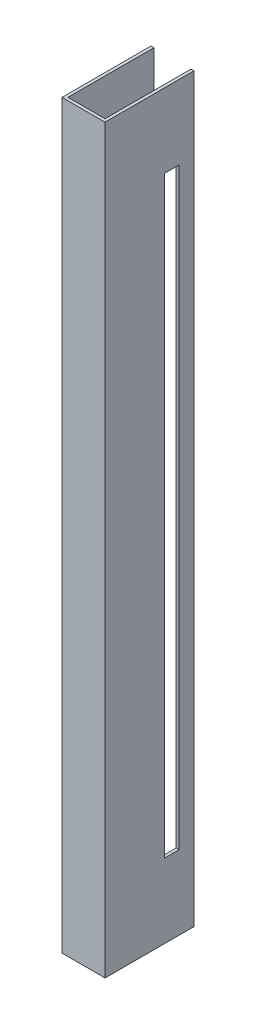
SolidWorks part; units mm, degrees
ref_plane "Front Plane" through (0, 0, 0) normal (0, 0, 1) x (1, 0, 0)
ref_plane "Top Plane" through (0, 0, 0) normal (0, 1, 0) x (1, 0, 0)
ref_plane "Right Plane" through (0, 0, 0) normal (1, 0, 0) x (0, 0, -1)
sketch "Sketch1" plane through (0, 0, 0) normal (0, 1, 0) x (1, 0, 0)
  line L0 (-25, -33) -> (-25, 25)
  line L1 (2, -35) -> (-27, -35)
  line L2 (2, -35) -> (2, 25)
  line L3 (2, 25) -> (0, 25)
  line L4 (-27, -35) -> (-27, 25)
  line L8 (0, -33) -> (0, 25)
  line L9 (0, -33) -> (-25, -33)
  line L10 (0, 23) -> (-25, 23) construction
  line L11 (-25, -33) -> (-25, 23) construction
  line L12 (0, -33) -> (0, 23) construction
  line L13 (-25, 25) -> (-27, 25)
  line L14 (2, 25) -> (-27, 25) construction
  point P0 (0, 0)
  dimension "D1" = 60
  dimension "D2" = 29
  dimension "D3" = 2
extrude "Boss-Extrude1" add sketch "Sketch1" along normal blind 500
sketch "Sketch2" plane through (2, 0, 0) normal (1, 0, 0) x (0, 0, -1)
  line L0 (-35, 500) -> (25, 500) construction
  line L1 (5, 450) -> (15, 450)
  line L2 (5, 450) -> (5, 50)
  line L3 (5, 50) -> (15, 50)
  line L4 (15, 450) -> (15, 50)
  line L5 (5, 450) -> (15, 50) construction
  line L6 (5, 50) -> (15, 450) construction
  line L7 (25, 500) -> (25, 0) construction
  point P0 (10, 250)
  dimension "D1" = 400
  dimension "D2" = 50
  dimension "D3" = 10
  dimension "D4" = 10
extrude "Cut-Extrude1" cut sketch "Sketch2" against normal through all both and the other way through all
